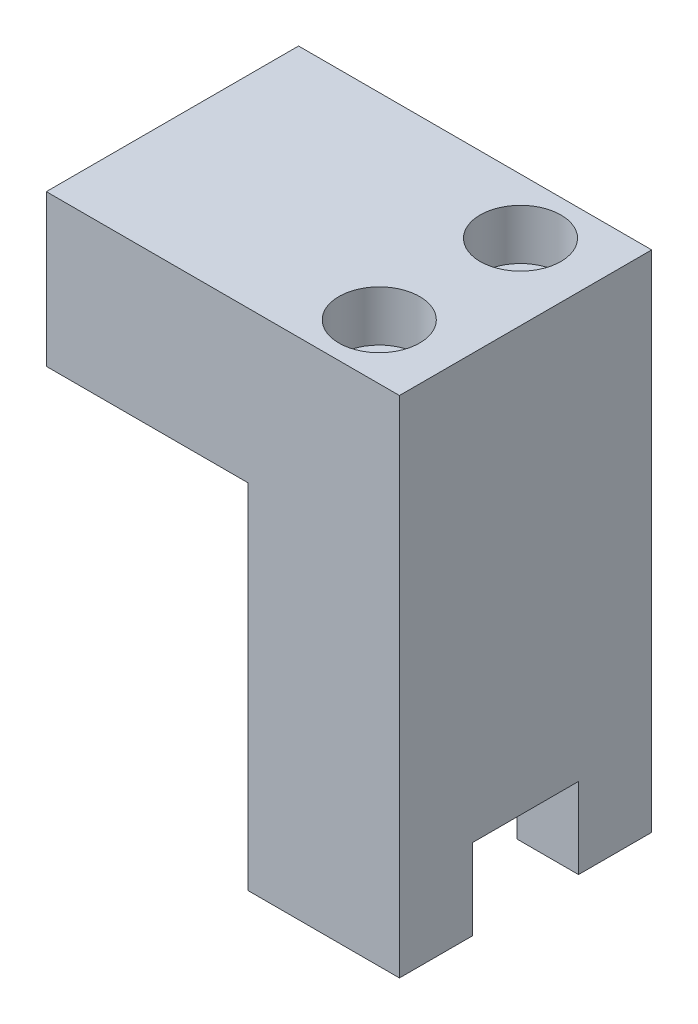
SolidWorks part; units mm, degrees
ref_plane "前视基准面" through (0, 0, 0) normal (0, 0, 1) x (1, 0, 0)
ref_plane "上视基准面" through (0, 0, 0) normal (0, 1, 0) x (1, 0, 0)
ref_plane "右视基准面" through (0, 0, 0) normal (1, 0, 0) x (0, 0, -1)
sketch "草图1" plane through (0, 0, 0) normal (0, 0, 1) x (1, 0, 0)
  line L8 (0, 0) -> (35, 0)
  line L10 (35, 0) -> (35, -50)
  line L11 (35, -50) -> (20, -50)
  line L12 (20, -50) -> (20, -15)
  line L13 (20, -15) -> (0, -15)
  line L14 (0, -15) -> (0, 0)
  dimension "D1" = 15
  dimension "D2" = 15
  dimension "D3" = 35
  dimension "D4" = 50
extrude "凸台-拉伸1" add sketch "草图1" along normal blind 25
sketch "草图2" plane through (0, 0, 0) normal (0, 1, 0) x (1, 0, 0)
  line L0 (27.5, -5.5) -> (27.5, -19.5) construction
  line L1 (20, -25) -> (35, -25) construction
  line L2 (0, -25) -> (0, 0) construction
  line L3 (27.5, -12.5) -> (0, -12.5) construction
  circle A0 centre (27.5, -5.5) radius 2.25
  circle A1 centre (27.5, -19.5) radius 2.25
  point P2 (0, -12.5)
  point P4 (0, 0)
  point P10 (0, 0)
  point P13 (27.5, -25)
  dimension "D1" = 4.5
  dimension "D2" = 14
extrude "切除-拉伸1" cut sketch "草图2" against normal through all
sketch "草图3" plane through (0, 0, 0) normal (0, 1, 0) x (1, 0, 0)
  circle A0 centre (27.5, -5.5) radius 4
  circle A1 centre (27.5, -19.5) radius 4
  dimension "D1" = 8
extrude "切除-拉伸2" cut sketch "草图3" against normal blind 5
sketch "草图4" plane through (35, 0, 0) normal (1, 0, 0) x (0, 0, -1)
  line L1 (-17.75, -58) -> (-7.25, -58)
  line L2 (-17.75, -58) -> (-17.75, -42)
  line L3 (-17.75, -42) -> (-7.25, -42)
  line L4 (-7.25, -58) -> (-7.25, -42)
  line L5 (-17.75, -58) -> (-7.25, -42) construction
  line L6 (-17.75, -42) -> (-7.25, -58) construction
  line L7 (-25, -50) -> (0, -50) construction
  point P0 (-12.5, -50)
  point P5 (-12.5, -50)
  point P7 (0, 0)
  dimension "D1" = 10.5
  dimension "D2" = 8
extrude "切除-拉伸5" cut sketch "草图4" against normal through all
